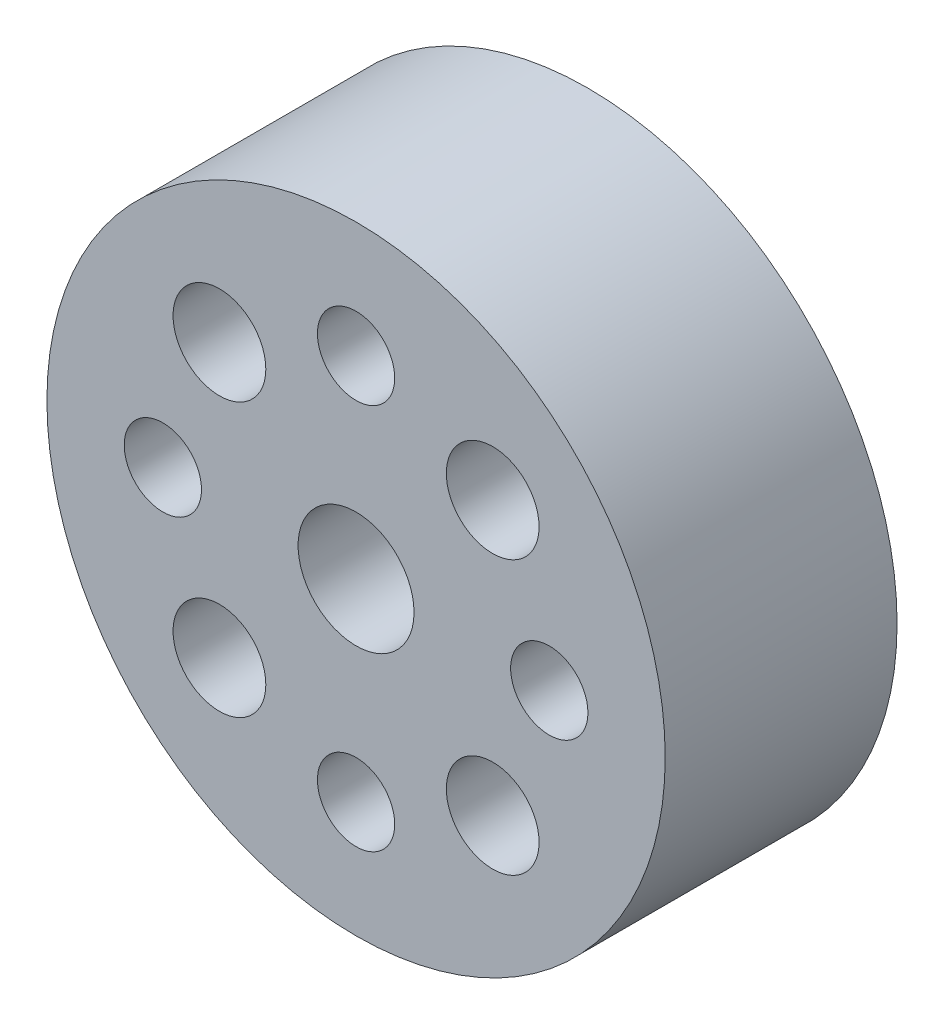
SolidWorks part; units mm, degrees
ref_plane "Ebene vorne" through (0, 0, 0) normal (0, 0, 1) x (1, 0, 0)
ref_plane "Ebene oben" through (0, 0, 0) normal (0, 1, 0) x (1, 0, 0)
ref_plane "Ebene rechts" through (0, 0, 0) normal (1, 0, 0) x (0, 0, -1)
sketch "Skizze1" plane through (0, 0, 0) normal (0, 0, 1) x (1, 0, 0)
  circle A0 centre (0, 0) radius 40
  dimension "D1" = 80
extrude "Aufsatz-Linear austragen1" add sketch "Skizze1" along normal blind 30
sketch "Skizze2" plane through (0, 0, 30) normal (0, 0, 1) x (1, 0, 0)
  line L0 (0, 40) -> (0, -40) construction
  line L1 (-40, 0) -> (40, 0) construction
  circle A0 centre (0, 0) radius 40 construction
  circle A1 centre (25, 0) radius 5
  circle A2 centre (0, -25) radius 5
  circle A3 centre (-25, 0) radius 5
  circle A4 centre (0, 25) radius 5
  point P18 (0, 0)
  dimension "D2" = 10
  dimension "D1" = 25
  dimension "D3" = 4
extrude "Schnitt-Linear austragen1" cut sketch "Skizze2" against normal blind 25
sketch "Skizze4" plane through (0, 0, 30) normal (0, 0, 1) x (1, 0, 0)
  line L0 (0, 0) -> (36.9528, 0) construction
  line L1 (0, 0) -> (17.6777, 17.6777) construction
  circle A0 centre (17.6777, 17.6777) radius 6
  circle A1 centre (17.6777, -17.6777) radius 6
  circle A2 centre (-17.6777, -17.6777) radius 6
  circle A3 centre (-17.6777, 17.6777) radius 6
  point P13 (0, 0)
  dimension "D2" = 12
  dimension "D1" = 25
  dimension "D3" = 45
  dimension "D4" = 4
extrude "Schnitt-Linear austragen5" cut sketch "Skizze4" against normal blind 25
sketch "Skizze5" plane through (0, 0, 30) normal (0, 0, 1) x (1, 0, 0)
  circle A0 centre (0, 0) radius 7.5
  dimension "D1" = 15
extrude "Schnitt-Linear austragen6" cut sketch "Skizze5" against normal blind 25
